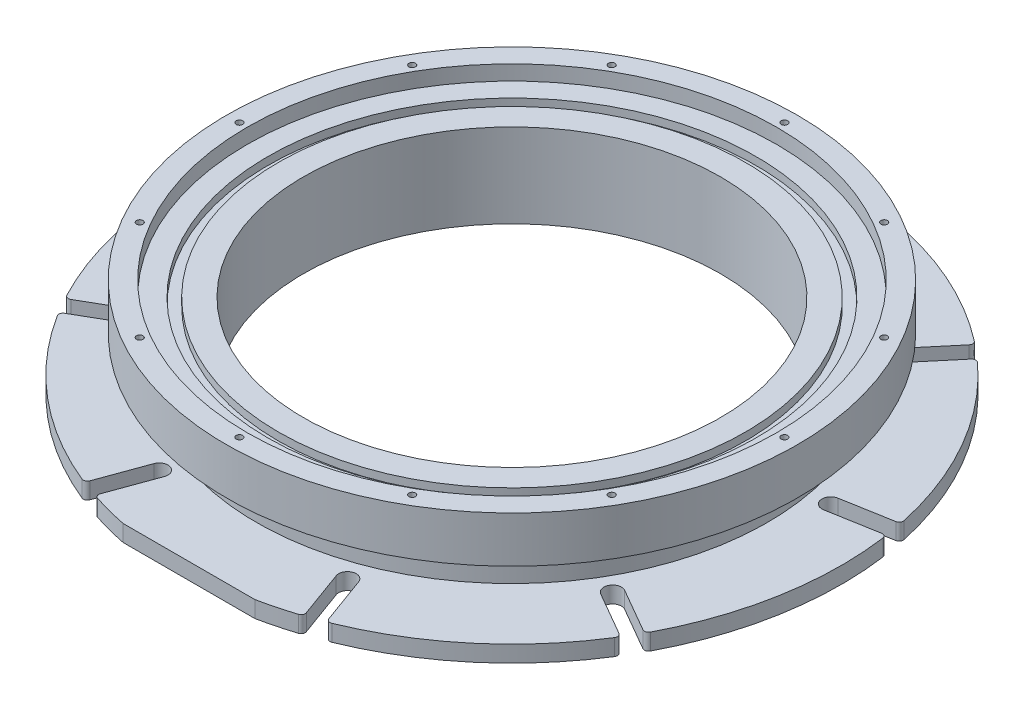
SolidWorks part; units mm, degrees
material "AISI 304"
ref_plane "Front" through (0, 0, 0) normal (0, 0, 1) x (1, 0, 0)
ref_plane "Top" through (0, 0, 0) normal (0, 1, 0) x (1, 0, 0)
ref_plane "Right" through (0, 0, 0) normal (1, 0, 0) x (0, 0, -1)
sketch "Sketch1" plane through (0, 0, 0) normal (0, 0, 1) x (1, 0, 0)
  line L0 (0, 0) -> (0, 38.1) construction
  line L2 (80.3783, 0) -> (127, 0)
  line L3 (127, 0) -> (127, 6.35)
  line L8 (80.3783, 32.34) -> (80.3783, 0)
  line L9 (80.3783, 32.34) -> (102, 32.34)
  line L12 (98.425, 6.35) -> (127, 6.35)
  line L14 (110, 20.32) -> (98.425, 20.32)
  line L15 (98.425, 20.32) -> (98.425, 6.35)
  line L16 (110, 38.1) -> (102, 38.1)
  line L17 (102, 38.1) -> (102, 32.34)
  line L18 (110, 38.1) -> (110, 20.32)
  dimension "D1" = 160.7566
  dimension "D2" = 254
  dimension "D3" = 5.76
  dimension "D4" = 220
  dimension "D5" = 38.1
  dimension "D6" = 204
  dimension "D7" = 6.35
  dimension "D8" = 13.97
  dimension "D9" = 196.85
revolve "Revolve1" add sketch "Sketch1" angle 360 about L0
hole_wizard "M3x0.5 Tapped Hole1" positions "Sketch2" profile "Sketch3" tap size "M3x0.5" standard "ANSI Metric"
sketch "Sketch2" plane through (0, 38.1, 0) normal (0, 1, 0) x (1, 0, 0)
  line L0 (0, 0) -> (0, 105) construction
  point P0 (0, 105)
  point P6 (52.5, 90.9327)
  point P7 (90.9327, 52.5)
  point P8 (105, 0)
  point P9 (90.9327, -52.5)
  point P10 (52.5, -90.9327)
  point P11 (0, -105)
  point P12 (-52.5, -90.9327)
  point P18 (-90.9327, -52.5)
  point P19 (-105, 0)
  point P20 (-90.9327, 52.5)
  point P21 (-52.5, 90.9327)
  dimension "D2" = 105
  dimension "D1" = 12
cosmetic thread "Hole Thread1" parameters "D1"=11.9888, "D2"=3
cosmetic thread "Hole Thread2" parameters "D1"=11.9888, "D2"=3
cosmetic thread "Hole Thread3" parameters "D1"=11.9888, "D2"=3
cosmetic thread "Hole Thread4" parameters "D1"=11.9888, "D2"=3
cosmetic thread "Hole Thread5" parameters "D1"=11.9888, "D2"=3
cosmetic thread "Hole Thread6" parameters "D1"=11.9888, "D2"=3
cosmetic thread "Hole Thread7" parameters "D1"=11.9888, "D2"=3
cosmetic thread "Hole Thread8" parameters "D1"=11.9888, "D2"=3
cosmetic thread "Hole Thread9" parameters "D1"=11.9888, "D2"=3
cosmetic thread "Hole Thread10" parameters "D1"=11.9888, "D2"=3
cosmetic thread "Hole Thread11" parameters "D1"=11.9888, "D2"=3
cosmetic thread "Hole Thread12" parameters "D1"=11.9888, "D2"=3
sketch "Sketch3" plane through (0, 38.1, -105) normal (1, 0, 0) x (0, 0, 1)
  line L0 (0, 0) -> (0, 14.2385)
  line L1 (0, 14.2385) -> (1.25, 13.4874)
  line L2 (1.25, 13.4874) -> (1.25, 0)
  line L5 (1.25, 0) -> (0, 0)
  line L10 (0, 14.2385) -> (-1.25, 13.4874) construction
  line L11 (0, -6.35) -> (0, 107.95) construction
  dimension "Tap Drill Dia." = 2.5
  dimension "Tap Drill Depth" = 13.4874
  dimension "Drill Angle" = 118
sketch "Sketch7" plane through (0, 0, 0) normal (0, 1, 0) x (1, 0, 0)
  line L1 (-25.4, -124.4341) -> (25.4, -124.4341)
  line L2 (-25.4, -124.4341) -> (-25.4, -127)
  line L3 (-25.4, -127) -> (25.4, -127)
  line L4 (25.4, -124.4341) -> (25.4, -127)
  circle A1 centre (0, 0) radius 127 construction
  dimension "D1" = 50.8
extrude "Cut-Extrude1" cut sketch "Sketch7" along normal up to next
sketch "Sketch10" plane through (0, 0, 0) normal (0, -1, 0) x (1, 0, 0)
  line L0 (0, -106.045) -> (0, 0) construction
  line L2 (-3.3782, -106.045) -> (-3.3782, -127)
  line L3 (-3.3782, -127) -> (3.3782, -127)
  line L4 (3.3782, -106.045) -> (3.3782, -127)
  arc A0 (-3.3782, -106.045) -> (3.3782, -106.045) centre (0, -106.045) cw
  circle A1 centre (0, 0) radius 127 construction
  circle A2 centre (0, 0) radius 98.425 construction
  circle A3 centre (0, 0) radius 98.425 construction
  circle A4 centre (0, -106.045) radius 4.7625 construction
  dimension "D1" = 106.045
  dimension "D2" = 3.3782
  dimension "D3" = 2.8575
  dimension "D4" = 9.525
extrude "Cut-Extrude2" cut sketch "Sketch10" against normal up to next
fillet "Fillet1" radius 1.5875 2 edges at (-3.3782, 3.175, -126.9551) (3.3782, 3.175, -126.9551)
pattern_circular "CirPattern1" count 9 over 360 about axis through (0, 0, 0) along (0, 1, 0) of "Cut-Extrude2", "Fillet1"
sketch "Sketch11" plane through (0, 32.34, 0) normal (0, 1, 0) x (1, 0, 0)
  circle A0 centre (0, 0) radius 90
  circle A1 centre (0, 0) radius 94
  dimension "D1" = 180
  dimension "D2" = 188
extrude "Cut-Extrude3" cut sketch "Sketch11" against normal blind 3
